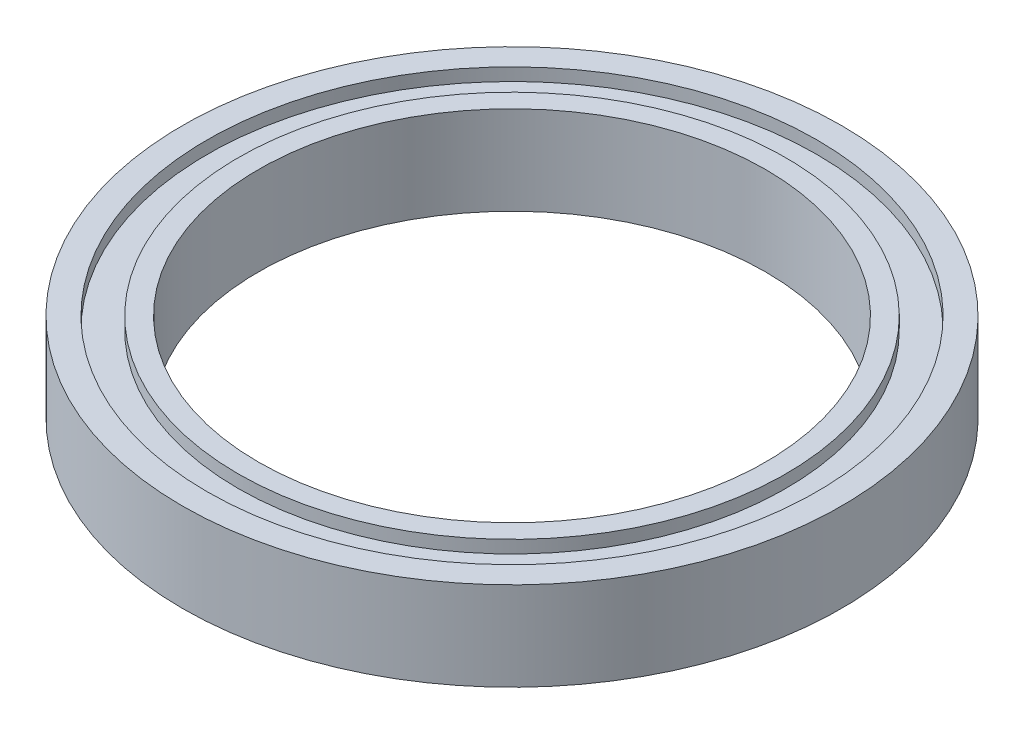
SolidWorks part; units mm, degrees
material "不锈钢 (铁素体)"
ref_plane "前视基准面" through (0, 0, 0) normal (0, 0, 1) x (1, 0, 0)
ref_plane "上视基准面" through (0, 0, 0) normal (0, 1, 0) x (1, 0, 0)
ref_plane "右视基准面" through (0, 0, 0) normal (1, 0, 0) x (0, 0, -1)
sketch "草图2" plane through (0, 0, 0) normal (0, 0, 1) x (1, 0, 0)
  line L0 (0, 0) -> (67.1689, 0) construction
  line L1 (0, 53.94) -> (0, 0) construction
  line L2 (26, -3.5) -> (26, 3.5)
  line L3 (26, 3.5) -> (24.05, 3.5)
  line L4 (24.05, 3.5) -> (24.05, 2.5)
  line L5 (24.05, 2.5) -> (21.605, 2.5)
  line L6 (21.605, 2.5) -> (21.605, 3.5)
  line L7 (21.605, 3.5) -> (20, 3.5)
  line L8 (20, 3.5) -> (20, -3.5)
  line L9 (21.605, -3.5) -> (20, -3.5)
  line L10 (21.605, -2.5) -> (21.605, -3.5)
  line L11 (24.05, -2.5) -> (21.605, -2.5)
  line L12 (24.05, -3.5) -> (24.05, -2.5)
  line L13 (26, -3.5) -> (24.05, -3.5)
  point P13 (20, 0)
  point P18 (26, 0)
  dimension "D1" = 7
  dimension "D2" = 52
  dimension "D3" = 40
  dimension "D4" = 43.21
  dimension "D5" = 48.1
  dimension "D6" = 1
revolve "旋转1" add sketch "草图2" angle 360 about L1
move or copy body "实体-移动/复制1" [suppressed] bodies to move or copy 106
